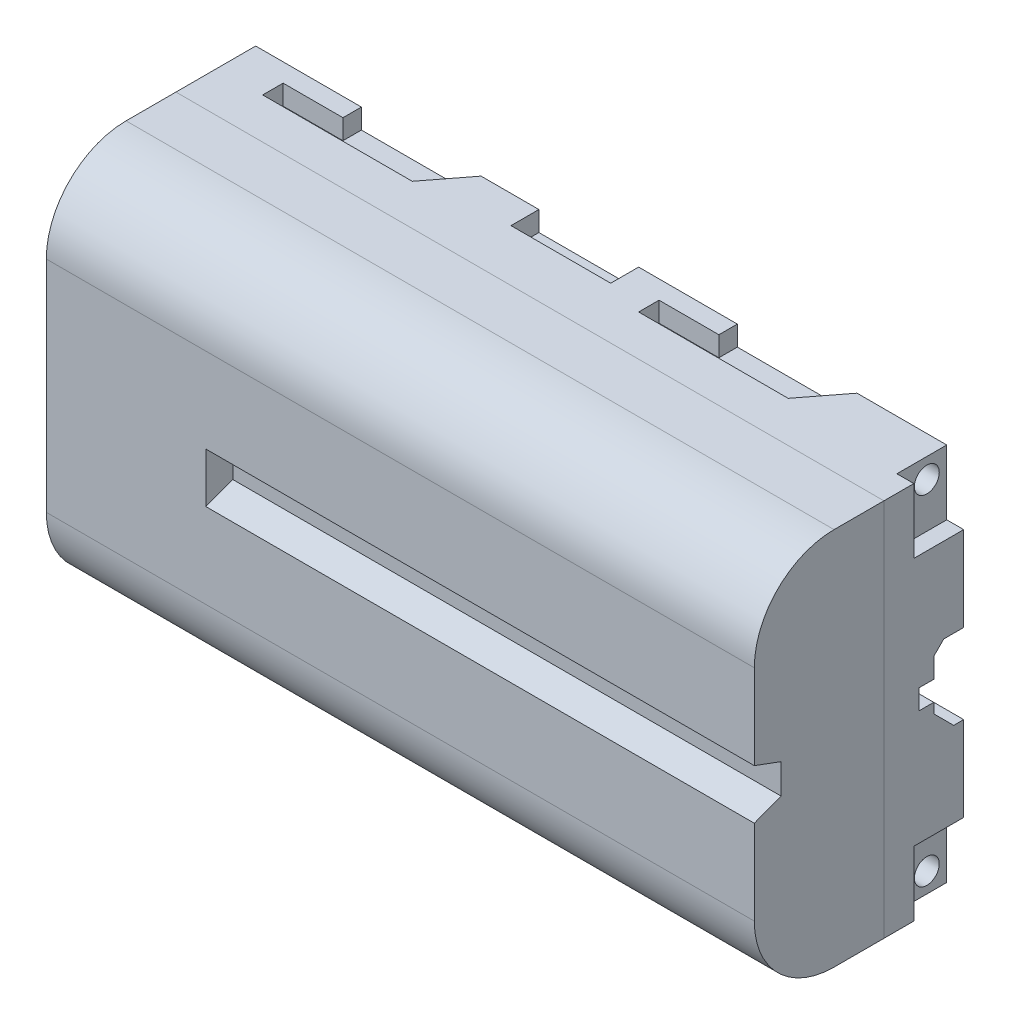
SolidWorks part; units mm, degrees
ref_plane "Спереди" through (0, 0, 0) normal (0, 0, 1) x (1, 0, 0)
ref_plane "Сверху" through (0, 0, 0) normal (0, 1, 0) x (1, 0, 0)
ref_plane "Справа" through (0, 0, 0) normal (1, 0, 0) x (0, 0, -1)
sketch "Эскиз1" plane through (0, 0, 0) normal (0, 0, 1) x (1, 0, 0)
  line L1 (0, 0) -> (71, 0)
  line L2 (0, 0) -> (0, 38)
  line L3 (0, 38) -> (71, 38)
  line L4 (71, 0) -> (71, 38)
  dimension "D1" = 38
  dimension "D2" = 71
extrude "Бобышка-Вытянуть1" add sketch "Эскиз1" along normal blind 8
sketch "Эскиз2" plane through (71, 0, 0) normal (1, 0, 0) x (0, 0, -1)
  line L0 (-8, 19) -> (0, 19) construction
  line L1 (0, 0) -> (-5, 0)
  line L2 (0, 0) -> (0, 6.5)
  line L3 (0, 6.5) -> (-5, 6.5)
  line L4 (-5, 0) -> (-5, 6.5)
  line L5 (-8, 0) -> (-8, 38) construction
  line L6 (0, 0) -> (0, 38) construction
  line L7 (-5, 38) -> (-5, 31.5)
  line L8 (0, 31.5) -> (-5, 31.5)
  line L9 (0, 38) -> (0, 31.5)
  line L10 (0, 38) -> (-5, 38)
  dimension "D1" = 5
  dimension "D2" = 6.5
extrude "Вырез-Вытянуть1" cut sketch "Эскиз2" against normal blind 1.7
sketch "Эскиз3" plane through (0, 0, 0) normal (0, -1, 0) x (1, 0, 0)
  line L0 (60.3, 0) -> (57.3, 3.9)
  line L1 (0, 0) -> (69.3, 0) construction
  line L2 (57.3, 3.9) -> (42.3, 3.9)
  line L3 (42.3, 3.9) -> (42.3, 1.85)
  line L4 (42.3, 1.85) -> (48.3, 1.85)
  line L5 (48.3, 1.85) -> (48.3, 0)
  line L6 (48.3, 0) -> (60.3, 0)
  line L7 (38.4, 0) -> (38.4, 2.8)
  line L8 (38.4, 2.8) -> (28.4, 2.8)
  line L9 (28.4, 2.8) -> (28.4, 0)
  line L10 (28.4, 0) -> (38.4, 0)
  line L11 (22.6, 0) -> (19.6, 3.9)
  line L12 (19.6, 3.9) -> (4.6, 3.9)
  line L13 (4.6, 3.9) -> (4.6, 1.85)
  line L14 (4.6, 1.85) -> (10.6, 1.85)
  line L15 (10.6, 1.85) -> (10.6, 0)
  line L16 (10.6, 0) -> (22.6, 0)
  line L17 (69.3, 0) -> (69.3, 5) construction
  dimension "D1" = 1.85
  dimension "D2" = 1.85
  dimension "D3" = 2.8
  dimension "D4" = 10
  dimension "D5" = 15
  dimension "D6" = 6
  dimension "D7" = 12
  dimension "D8" = 3.9
  dimension "D9" = 9
  dimension "D10" = 9.9
  dimension "D11" = 3.9
  dimension "D12" = 15
  dimension "D13" = 6
  dimension "D14" = 27.8
extrude "Вырез-Вытянуть2" cut sketch "Эскиз3" against normal blind 2
ref_plane "Плоскость1" through (0, 19, 0) normal (0, -1, 0) x (-1, 0, 0)
mirror "Зеркальное отражение1" about plane through (0, 19, 0) normal (0, -1, 0) of "Вырез-Вытянуть2"
sketch "Эскиз4" plane through (0, 0, 0) normal (0, 0, -1) x (-1, 0, 0)
  line L0 (0, 19) -> (-71, 19) construction
  line L1 (0, 38) -> (0, 0) construction
  line L2 (-71, 6.5) -> (-71, 31.5) construction
  line L4 (-9.6, 21.2) -> (0, 21.2)
  line L5 (-9.6, 21.2) -> (-9.6, 16.8)
  line L6 (-9.6, 16.8) -> (0, 16.8)
  line L7 (0, 21.2) -> (0, 16.8)
  line L8 (-9.6, 21.2) -> (0, 16.8) construction
  line L9 (-9.6, 16.8) -> (0, 21.2) construction
  line L10 (-38.6, 21.2) -> (-28.6, 21.2)
  line L11 (-38.6, 21.2) -> (-38.6, 16.8)
  line L12 (-38.6, 16.8) -> (-28.6, 16.8)
  line L13 (-28.6, 21.2) -> (-28.6, 16.8)
  line L14 (-38.6, 21.2) -> (-28.6, 16.8) construction
  line L15 (-38.6, 16.8) -> (-28.6, 21.2) construction
  point P6 (-4.8, 19)
  point P11 (-33.6, 19)
  dimension "D1" = 4.4
  dimension "D2" = 9.6
  dimension "D3" = 10
  dimension "D4" = 19
extrude "Вырез-Вытянуть3" cut sketch "Эскиз4" against normal blind 3
sketch "Эскиз5" plane through (0, 0, 0) normal (0, 0, -1) x (-1, 0, 0)
  line L0 (-71, 19) -> (-53.9284, 19) construction
  line L1 (-71, 6.5) -> (-71, 31.5) construction
  line L2 (-38.6, 21.2) -> (-38.6, 16.8) construction
  line L3 (-50.1, 23) -> (-41.9, 23)
  line L4 (-50.1, 23) -> (-50.1, 15)
  line L5 (-50.1, 15) -> (-41.9, 15)
  line L6 (-41.9, 23) -> (-41.9, 15)
  line L7 (-50.1, 23) -> (-41.9, 15) construction
  line L8 (-50.1, 15) -> (-41.9, 23) construction
  point P4 (-46, 19)
  dimension "D1" = 8.2
  dimension "D2" = 8
  dimension "D3" = 3.3
extrude "Вырез-Вытянуть4" cut sketch "Эскиз5" against normal blind 2.4
sketch "Эскиз7" plane through (71, 0, 0) normal (1, 0, 0) x (0, 0, -1)
  line L0 (0, 19) -> (-11.4639, 19) construction
  line L1 (0, 6.5) -> (0, 31.5) construction
  line L2 (-3, 18) -> (-3, 17)
  line L3 (-3, 20) -> (-4.5, 20)
  line L5 (-3, 18) -> (-4.5, 18)
  line L6 (-4.5, 20) -> (-4.5, 18)
  line L7 (-3, 20) -> (-4.5, 18) construction
  line L8 (-3, 18) -> (-4.5, 20) construction
  line L9 (-3, 17) -> (-1, 15)
  line L10 (-1, 15) -> (0, 15)
  line L11 (0, 15) -> (0, 23)
  line L12 (0, 23) -> (-2, 23)
  line L13 (-2, 23) -> (-3, 22)
  line L14 (-3, 22) -> (-3, 20)
  point P4 (-3.75, 19)
  point P9 (-4.5, 19)
  dimension "D1" = 2
  dimension "D2" = 4.5
  dimension "D3" = 1
  dimension "D4" = 2
  dimension "D5" = 8
  dimension "D6" = 1
  dimension "D7" = 2
  dimension "D8" = 3
extrude "Вырез-Вытянуть5" cut sketch "Эскиз7" against normal blind 7.5
sketch "Эскиз8" plane through (63.5, 0, 0) normal (1, 0, 0) x (0, 0, -1)
  line L0 (0, 23) -> (-2, 23) construction
  line L1 (-2, 23) -> (-3, 22) construction
  line L2 (-3, 22) -> (-3, 20) construction
  line L3 (0, 23) -> (-2, 23)
  line L4 (-2, 23) -> (-3, 22)
  line L5 (-3, 22) -> (-3, 20)
  line L6 (0, 23) -> (0, 20)
  line L7 (0, 15) -> (0, 23) construction
  line L8 (0, 20) -> (-3, 20)
extrude "Вырез-Вытянуть6" cut sketch "Эскиз8" against normal up to surface (13.4 mm away) up to face at (50.1, 19, 1.2)
sketch "Эскиз9" plane through (0, 0, 0) normal (0, 0, -1) x (-1, 0, 0)
  line L1 (-63.5, 20) -> (-58.5, 20)
  line L2 (-63.5, 20) -> (-63.5, 16)
  line L3 (-63.5, 16) -> (-58.5, 16)
  line L4 (-58.5, 20) -> (-58.5, 16)
  dimension "D1" = 4
  dimension "D2" = 5
extrude "Вырез-Вытянуть7" cut sketch "Эскиз9" against normal blind 1.6
sketch "Эскиз11" plane through (0, 19, 0) normal (0, -1, 0) x (-1, 0, 0)
  line L0 (-10.6, 0) -> (-22.6, 0) construction
  line L1 (-20.6, 0) -> (-11.6, 0)
  line L2 (-20.6, 0) -> (-20.6, -3)
  line L3 (-20.6, -3) -> (-17.1, -3)
  line L4 (-11.6, 0) -> (-17.1, -3)
  line L5 (-28.6, -3) -> (-28.6, 0) construction
  dimension "D1" = 9
  dimension "D2" = 3.5
  dimension "D3" = 3
  dimension "D4" = 8
extrude "Вырез-Вытянуть8" cut sketch "Эскиз11" against normal up to surface and the other way up to surface up to face at (33.6, 21.2, 1.5) other way up to face at (33.6, 16.8, 1.5)
sketch "Эскиз12" plane through (69.3, 0, 0) normal (1, 0, 0) x (0, 0, -1)
  line L0 (-2.8, 38) -> (0, 38) construction
  line L1 (0, 31.5) -> (0, 38) construction
  line L2 (-8, 19) -> (-5.2267, 19) construction
  line L3 (-8, 0) -> (-8, 38) construction
  circle A0 centre (-2, 36) radius 1.25
  circle A1 centre (-2, 2) radius 1.25
  point P2 (-1.4, 38)
  dimension "D1" = 2
  dimension "D3" = 2.5
  dimension "D2" = 2
extrude "Вырез-Вытянуть9" cut sketch "Эскиз12" against normal blind 7
sketch "Эскиз13" plane through (0, 0, 8) normal (0, 0, 1) x (1, 0, 0)
  line L4 (0, 38) -> (0, 0)
  line L5 (0, 0) -> (71, 0)
  line L6 (71, 0) -> (71, 38)
  line L7 (71, 38) -> (0, 38)
  line L8 (0, 38) -> (0, 0)
  line L9 (0, 0) -> (71, 0)
  line L10 (71, 0) -> (71, 38)
  line L11 (71, 38) -> (0, 38)
  dimension "D1" = 0
extrude "Бобышка-Вытянуть2" add sketch "Эскиз13" along normal offset from surface (13 mm away) 21 separate body up to face at (16.1, 19, 0)
fillet "Скругление1" radius 8 2 edges at (35.5, 0, 21) (35.5, 38, 21)
sketch "Эскиз14" plane through (71, 0, 0) normal (1, 0, 0) x (0, 0, -1)
  line L0 (-8, 19) -> (-28.6, 19) construction
  line L1 (-8, 0) -> (-8, 38) construction
  line L2 (-21, 16.5) -> (-21, 21.5)
  line L3 (-21, 30) -> (-21, 8) construction
  line L4 (-21, 21.5) -> (-18.3, 20.5)
  line L5 (-18.3, 20.5) -> (-18.3, 17.5)
  line L6 (-18.3, 17.5) -> (-21, 16.5)
  point P8 (-21, 19)
  point P11 (-18.3, 19)
  dimension "D1" = 3
  dimension "D2" = 5
  dimension "D3" = 2.7
extrude "Вырез-Вытянуть10" cut sketch "Эскиз14" against normal blind 55
